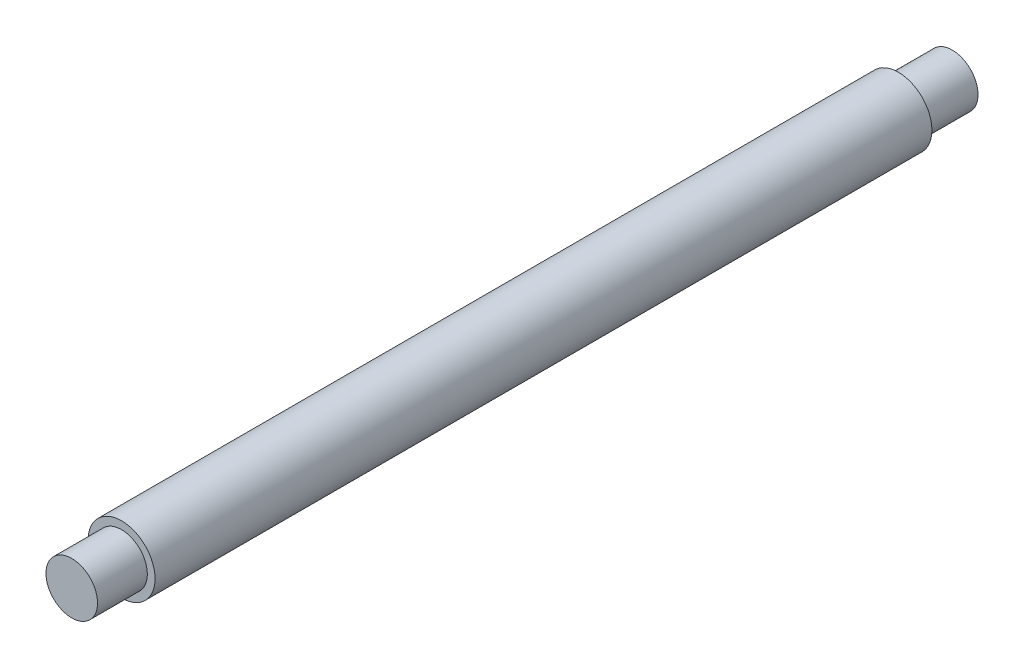
SolidWorks part; units mm, degrees
ref_plane "前视基准面" through (0, 0, 0) normal (0, 0, 1) x (1, 0, 0)
ref_plane "上视基准面" through (0, 0, 0) normal (0, 1, 0) x (1, 0, 0)
ref_plane "右视基准面" through (0, 0, 0) normal (1, 0, 0) x (0, 0, -1)
sketch "草图1" plane through (0, 0, 0) normal (0, 0, 1) x (1, 0, 0)
  circle A0 centre (0, 0) radius 1.925
  dimension "D1" = 3.85
extrude "凸台-拉伸1" add sketch "草图1" along normal blind 3.72
sketch "草图2" plane through (0, 0, 0) normal (0, 0, -1) x (-1, 0, 0)
  circle A0 centre (0, 0) radius 2.5
  dimension "D1" = 5
extrude "凸台-拉伸2" add sketch "草图2" along normal blind 58 contours A0
sketch "草图3" plane through (0, 0, -58) normal (0, 0, -1) x (-1, 0, 0)
  circle A0 centre (0, 0) radius 1.925
  dimension "D1" = 3.85
extrude "凸台-拉伸3" add sketch "草图3" along normal blind 4.02
